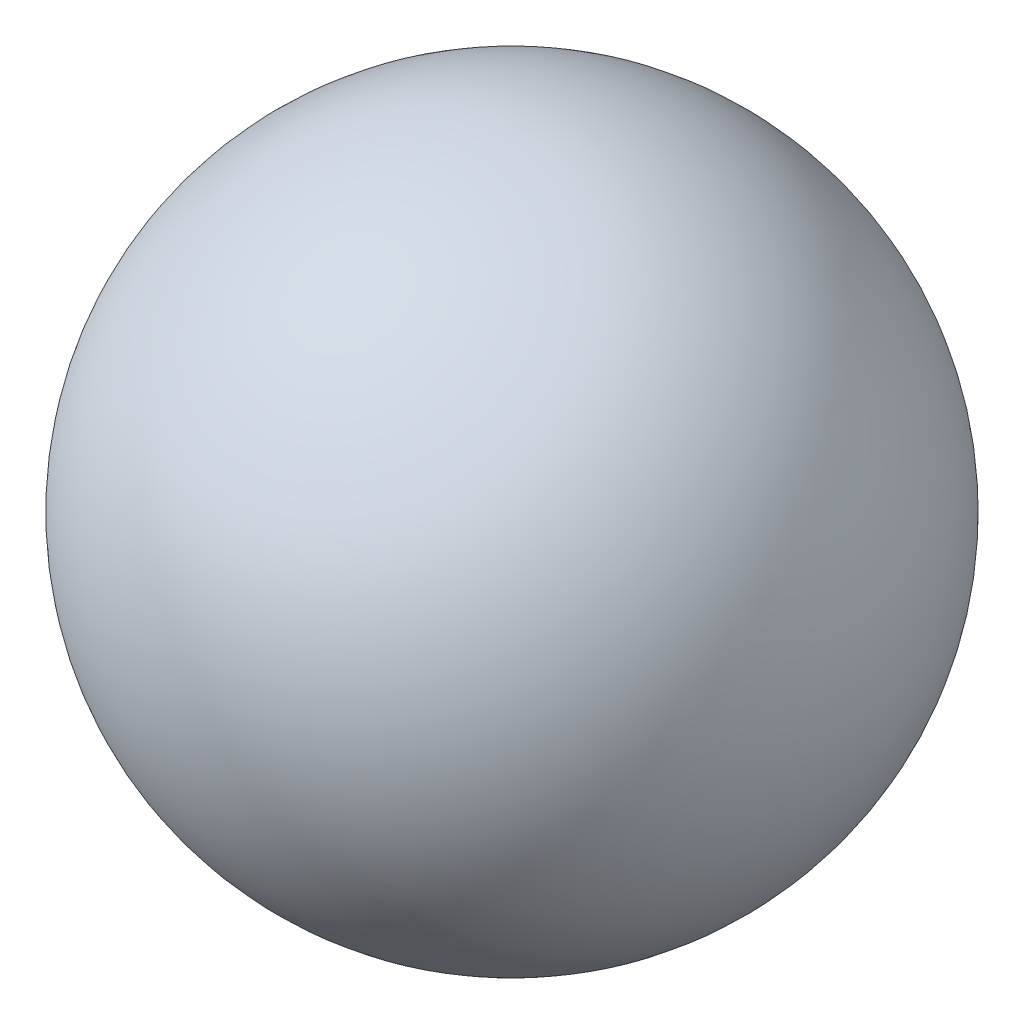
SolidWorks part; units mm, degrees
material "Alloy Steel (SS)"
ref_plane "Front Plane" through (0, 0, 0) normal (0, 0, 1) x (1, 0, 0)
ref_plane "Top Plane" through (0, 0, 0) normal (0, 1, 0) x (1, 0, 0)
ref_plane "Right Plane" through (0, 0, 0) normal (1, 0, 0) x (0, 0, -1)
sketch "Sketch1" plane through (0, 0, 0) normal (0, 0, 1) x (1, 0, 0)
  line L0 (0, -25.4) -> (0, 25.4) construction
  line L1 (0, -25.4) -> (0, 25.4)
  arc A0 (0, -25.4) -> (0, 25.4) centre (0, 0) ccw
  point P3 (0, 0)
  dimension "D1" = 50.8
revolve "Revolve1" add sketch "Sketch1" angle 360 about L0
